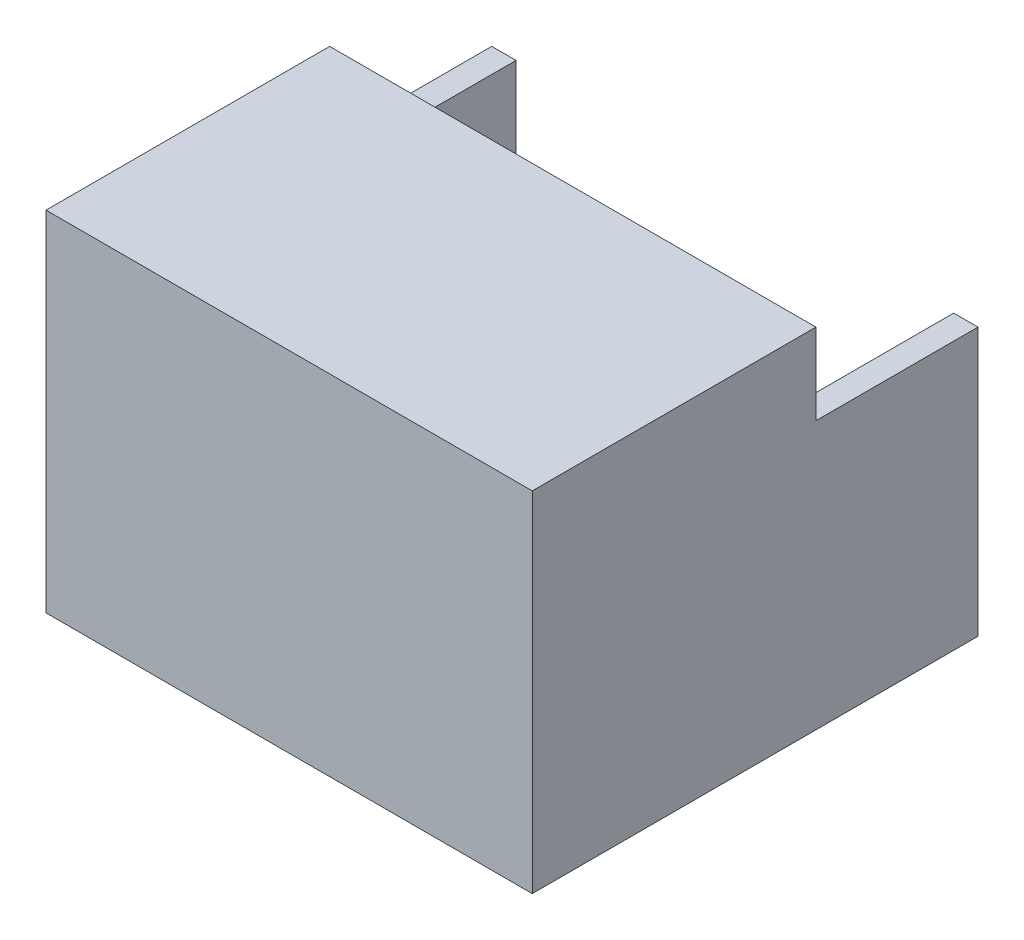
SolidWorks part; units mm, degrees
ref_plane "Ön Düzlem" through (0, 0, 0) normal (0, 0, 1) x (1, 0, 0)
ref_plane "Üst Düzlem" through (0, 0, 0) normal (0, 1, 0) x (1, 0, 0)
ref_plane "Sağ Düzlem" through (0, 0, 0) normal (1, 0, 0) x (0, 0, -1)
sketch "Çizim1" plane through (0, 0, 0) normal (0, 0, 1) x (1, 0, 0)
  line L0 (3, 3) -> (3, 40.0377)
  line L1 (0, 0) -> (60, 0)
  line L2 (0, 0) -> (0, 43.0377)
  line L3 (0, 43.0377) -> (60, 43.0377)
  line L4 (60, 0) -> (60, 43.0377)
  line L5 (3, 40.0377) -> (57, 40.0377)
  line L6 (57, 3) -> (57, 40.0377)
  line L7 (3, 3) -> (57, 3)
  dimension "D1" = 60
  dimension "D2" = 3
extrude "Yükseklik-Ekstrüzyon1" add sketch "Çizim1" along normal blind 110
sketch "Çizim2" plane through (0, 43.0377, 0) normal (0, 1, 0) x (1, 0, 0)
  line L0 (60, -110) -> (60, 0) construction
  line L1 (0, 0) -> (60, 0)
  line L2 (0, 0) -> (0, -20)
  line L3 (0, -20) -> (60, -20)
  line L4 (60, 0) -> (60, -20)
  dimension "D1" = 20
extrude "Kes-Ekstrüzyon1" cut sketch "Çizim2" against normal blind 10
sketch "Çizim3" plane through (0, 0, 110) normal (0, 0, 1) x (1, 0, 0)
  line L1 (0, 43.0377) -> (60, 43.0377)
  line L2 (0, 43.0377) -> (0, 0)
  line L3 (0, 0) -> (60, 0)
  line L4 (60, 43.0377) -> (60, 0)
extrude "Yükseklik-Ekstrüzyon2" add sketch "Çizim3" against normal blind 10
sketch "Çizim4" plane through (0, 43.0377, 0) normal (0, 1, 0) x (1, 0, 0)
  line L0 (60, -110) -> (60, -20) construction
  line L1 (0, -110) -> (60, -110)
  line L2 (0, -110) -> (0, -55)
  line L3 (0, -55) -> (60, -55)
  line L4 (60, -110) -> (60, -55)
  dimension "D1" = 55
extrude "Kes-Ekstrüzyon2" cut sketch "Çizim4" against normal blind 70
sketch "Çizim5" plane through (0, 0, 55) normal (0, 0, 1) x (1, 0, 0)
  line L1 (0, 43.0377) -> (60, 43.0377)
  line L2 (0, 43.0377) -> (0, 0)
  line L3 (0, 0) -> (60, 0)
  line L4 (60, 43.0377) -> (60, 0)
extrude "Yükseklik-Ekstrüzyon3" add sketch "Çizim5" against normal blind 5
